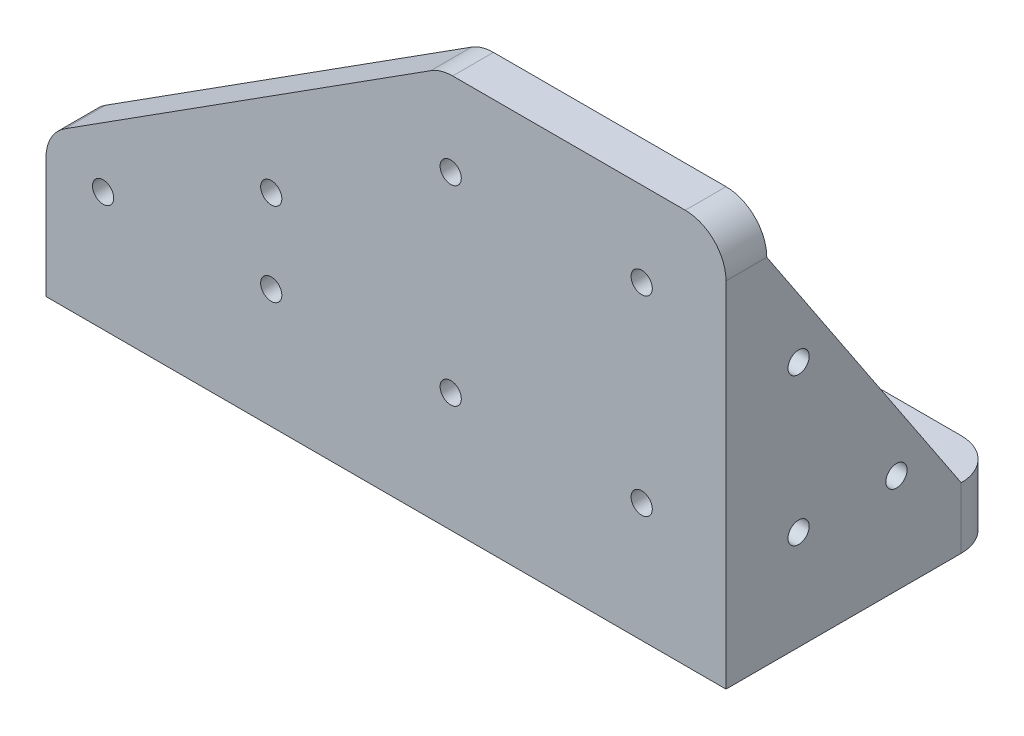
SolidWorks part; units mm, degrees
ref_plane "Front Plane" through (0, 0, 0) normal (0, 0, 1) x (1, 0, 0)
ref_plane "Top Plane" through (0, 0, 0) normal (0, 1, 0) x (1, 0, 0)
ref_plane "Right Plane" through (0, 0, 0) normal (1, 0, 0) x (0, 0, -1)
sketch "Sketch1" plane through (0, 0, 0) normal (0, 1, 0) x (1, 0, 0)
  line L0 (-33.2623, -33.2623) -> (-132.3305, -33.2623)
  line L1 (-33.2623, -33.2623) -> (34.4076, -33.2623)
  line L3 (-33.2623, 34.4076) -> (24.4076, 34.4076)
  line L4 (34.4076, -33.2623) -> (34.4076, 24.4076)
  line L5 (-33.2623, -33.2623) -> (34.4076, 34.4076) construction
  line L6 (-35.5924, 34.4076) -> (34.4076, -33.2623) construction
  line L7 (-132.3305, -33.2623) -> (-132.3305, -19.4828)
  line L8 (-126.7507, -10.5127) -> (-37.6825, 33.3777)
  line L9 (-33.2623, 13.2594) -> (-99.7071, -19.4828) construction
  line L14 (-21.25, -21.25) -> (21.25, 21.25) construction
  line L15 (-33.2623, 13.2594) -> (-99.7071, -19.4828) construction
  line L16 (-31.892, 10.4787) -> (-98.3368, -22.2635)
  line L17 (-34.6326, 16.0401) -> (-101.0773, -16.7021)
  line L18 (-122.3305, -19.4828) -> (-33.2623, -19.4828) construction
  line L19 (-33.2623, -19.4828) -> (-33.2623, 24.4076) construction
  line L20 (-122.3305, -19.4828) -> (-33.2623, 24.4076) construction
  line L21 (-123.7007, -16.7021) -> (-34.6326, 27.1883)
  line L22 (-120.9602, -22.2635) -> (-31.892, 21.6269)
  line L23 (-77.0836, -19.4828) -> (-33.2623, 2.1112) construction
  line L24 (-78.3712, -16.8698) -> (-34.5499, 4.7242)
  line L25 (-75.796, -22.0958) -> (-31.9747, -0.5018)
  arc A0 (24.4076, 34.4076) -> (34.4076, 24.4076) centre (24.4076, 24.4076) cw
  arc A1 (-37.6825, 33.3777) -> (-33.2623, 34.4076) centre (-33.2623, 24.4076) cw
  arc A2 (-132.3305, -19.4828) -> (-126.7507, -10.5127) centre (-122.3305, -19.4828) cw
  arc A3 (-123.7007, -16.7021) -> (-120.9602, -22.2635) centre (-122.3305, -19.4828) ccw
  arc A4 (-31.892, 21.6269) -> (-34.6326, 27.1883) centre (-33.2623, 24.4076) ccw
  arc A5 (-31.892, 10.4787) -> (-34.6326, 16.0401) centre (-33.2623, 13.2594) ccw
  arc A6 (-101.0773, -16.7021) -> (-98.3368, -22.2635) centre (-99.7071, -19.4828) ccw
  arc A7 (-78.3712, -16.8698) -> (-75.796, -22.0958) centre (-77.0836, -19.4828) ccw
  arc A8 (-31.9747, -0.5018) -> (-34.5499, 4.7242) centre (-33.2623, 2.1112) ccw
  point P0 (0, 0)
  point P16 (-132.3305, -13.2623)
  point P17 (0, 0)
  point P20 (-66.4847, -3.1117)
  point P27 (-55.173, -8.6858)
  point P32 (-77.7964, 2.4624)
  dimension "D3" = 10
  dimension "D4" = 10
  dimension "D1" = 70
  dimension "D2" = 20
  dimension "D5" = 90
  dimension "D6" = 10
extrude "Boss-Extrude1" add sketch "Sketch1" along normal blind 15
sketch "Sketch2" plane through (0, 15, 0) normal (0, 1, 0) x (1, 0, 0)
  line L0 (31.4787, 31.4787) -> (-33.2623, -33.2623) construction
  line L1 (-132.3305, -33.2623) -> (34.4076, -33.2623) construction
  line L2 (-21.25, 17.7145) -> (-17.7145, 21.25)
  line L3 (-21.25, -21.25) -> (21.25, -21.25)
  line L4 (-21.25, -21.25) -> (-21.25, 21.25)
  line L5 (-21.25, 21.25) -> (21.25, 21.25)
  line L6 (21.25, -21.25) -> (21.25, 21.25)
  line L7 (-21.25, -21.25) -> (21.25, 21.25) construction
  line L8 (-21.25, 21.25) -> (21.25, -21.25) construction
  line L9 (17.7145, -21.25) -> (21.25, -17.7145)
  line L10 (-21.25, 0) -> (21.25, 0) construction
  line L11 (17.7145, 21.25) -> (21.25, 17.7145)
  line L12 (-21.25, -17.7145) -> (-17.7145, -21.25)
  arc A0 (34.4076, 24.4076) -> (24.4076, 34.4076) centre (24.4076, 24.4076) ccw construction
  point P7 (0, 0)
  dimension "D1" = 42.5
  dimension "D2" = 5
  dimension "D3" = 45
  dimension "D4" = 45
extrude "Cut-Extrude1" cut sketch "Sketch2" against normal blind 10 contours L4 L12 L3 L9 L6 L11 L5 L2
sketch "Sketch4" plane through (0, 5, 0) normal (0, 1, 0) x (1, 0, 0)
  line L4 (-15.25, -15.25) -> (15.25, -15.25) construction
  line L5 (-15.25, -15.25) -> (-15.25, 15.25) construction
  line L6 (-15.25, 15.25) -> (15.25, 15.25) construction
  line L7 (15.25, -15.25) -> (15.25, 15.25) construction
  line L8 (-15.25, -15.25) -> (15.25, 15.25) construction
  line L9 (-15.25, 15.25) -> (15.25, -15.25) construction
  circle A0 centre (0, 0) radius 15
  circle A1 centre (-15.25, -15.25) radius 1.6
  circle A2 centre (-15.25, 15.25) radius 1.6
  circle A3 centre (15.25, 15.25) radius 1.6
  circle A4 centre (15.25, -15.25) radius 1.6
  dimension "D1" = 30
  dimension "D2" = 30.5
extrude "Cut-Extrude2" cut sketch "Sketch4" against normal blind 10
sketch "Sketch5" plane through (0, 0, 33.2623) normal (0, 0, 1) x (1, 0, 0)
  line L0 (-132.3305, 15) -> (-132.3305, 29.5157)
  line L1 (-127.7059, 37.9481) -> (-37.9896, 95.1403)
  line L2 (-32.6142, 96.708) -> (24.4076, 96.708)
  line L3 (34.4076, 86.708) -> (34.4076, 15)
  line L4 (-132.3305, 15) -> (34.4076, 15)
  arc A0 (24.4076, 96.708) -> (34.4076, 86.708) centre (24.4076, 86.708) cw
  arc A1 (-37.9896, 95.1403) -> (-32.6142, 96.708) centre (-32.6142, 86.708) cw
  arc A2 (-132.3305, 29.5157) -> (-127.7059, 37.9481) centre (-122.3305, 29.5157) cw
  point P12 (-35.5305, 96.708)
  point P15 (-132.3305, 35)
  dimension "D3" = 10
  dimension "D1" = 96.8
  dimension "D2" = 20
extrude "Boss-Extrude2" add sketch "Sketch5" against normal blind 10
sketch "Sketch6" plane through (34.4076, 0, 0) normal (1, 0, 0) x (0, 0, -1)
  line L0 (-23.2623, 86.708) -> (24.4076, 15)
  line L1 (24.4076, 15) -> (-23.2623, 15)
  line L2 (-23.2623, 15) -> (-23.2623, 86.708)
extrude "Boss-Extrude3" add sketch "Sketch6" against normal blind 10
sketch "Sketch7" plane through (0, 0, 23.2623) normal (0, 0, -1) x (-1, 0, 0)
  line L0 (-31.4787, 93.779) -> (47.3003, 15) construction
  line L1 (37.6825, 15) -> (126.7507, 15) construction
  arc A0 (-24.4076, 96.708) -> (-34.4076, 86.708) centre (-24.4076, 86.708) ccw construction
  circle A1 centre (-13.7328, 76.0332) radius 2.6
  circle A2 centre (33.1018, 29.1986) radius 2.6
  circle A3 centre (33.1018, 76.0332) radius 2.6
  circle A4 centre (-13.7328, 29.1986) radius 2.6
  circle A5 centre (118.329, 29.1986) radius 2.6
  circle A6 centre (77.1044, 29.1986) radius 2.6
  circle A7 centre (77.1044, 49.6678) radius 2.6
extrude "Cut-Extrude3" cut sketch "Sketch7" against normal blind 10
sketch "Sketch8" plane through (24.4076, 0, 0) normal (-1, 0, 0) x (0, 0, 1)
  line L0 (-24.4076, 15) -> (23.2623, 86.708) construction
  line L1 (-8.5405, 24.4177) -> (15.4674, 24.4177) construction
  line L2 (15.4674, 24.4177) -> (15.4674, 60.5318) construction
  circle A0 centre (15.4674, 24.4177) radius 2.6
  circle A1 centre (15.4674, 60.5318) radius 2.6
  circle A3 centre (-8.5405, 24.4177) radius 2.6
  point P8 (16.3531, 24.4177)
  dimension "D1" = 8
  dimension "D2" = 8
extrude "Cut-Extrude4" cut sketch "Sketch8" against normal blind 10
